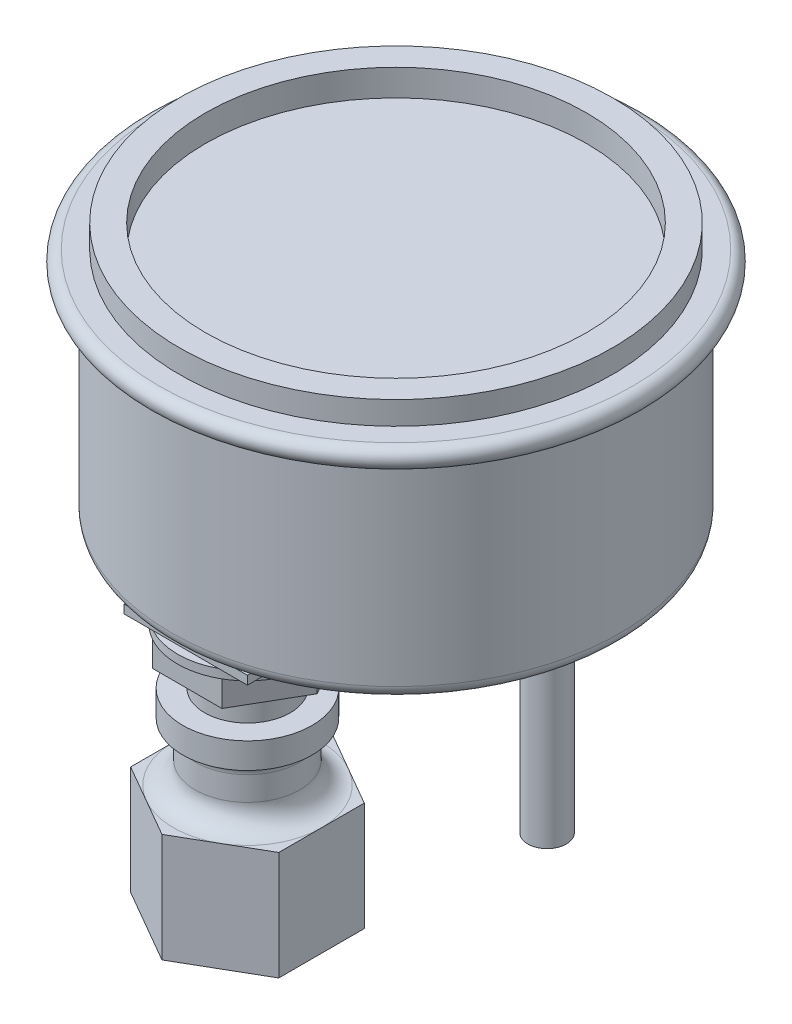
SolidWorks part; units mm, degrees
ref_plane "Front Plane" through (0, 0, 0) normal (0, 0, 1) x (1, 0, 0)
ref_plane "Top Plane" through (0, 0, 0) normal (0, 1, 0) x (1, 0, 0)
ref_plane "Right Plane" through (0, 0, 0) normal (1, 0, 0) x (0, 0, -1)
sketch "Sketch1" plane through (0, 0, 0) normal (0, 0, 1) x (1, 0, 0)
  line L0 (0, 0) -> (0, 26.8)
  line L1 (0, 26.8) -> (22.25, 26.8)
  line L2 (22.25, 26.8) -> (22.25, 29.9)
  line L3 (22.25, 29.9) -> (25.3, 29.9)
  line L4 (25.3, 29.9) -> (25.3, 27.2)
  line L5 (25.3, 27.2) -> (27.65, 27.2)
  line L6 (27.65, 24.8) -> (26.2, 24.8)
  line L7 (26.2, 24.8) -> (26.2, 1.5)
  line L8 (24.7, 0) -> (0, 0)
  line L9 (0, -4.0696) -> (0, 24.0575) construction
  arc A0 (27.65, 27.2) -> (27.65, 24.8) centre (27.65, 26) cw
  arc A1 (26.2, 1.5) -> (24.7, 0) centre (24.7, 1.5) cw
  point P15 (28.85, 26)
  dimension "D4" = 1.2
  dimension "D9" = 1.5
  dimension "D1" = 44.5
  dimension "D2" = 50.6
  dimension "D3" = 57.7
  dimension "D5" = 3.1
  dimension "D6" = 2.7
  dimension "D7" = 29.9
  dimension "D8" = 52.4
revolve "Revolve1" add sketch "Sketch1" angle 360 about L9
sketch "Sketch2" plane through (0, 0, 0) normal (0, -1, 0) x (1, 0, 0)
  line L0 (0, 0) -> (-17.65, 0) construction
  line L1 (0, 0) -> (0, -17.65) construction
  circle A2 centre (-17.65, 0) radius 4.3
  circle A3 centre (0, -17.65) radius 4.3
  circle A4 centre (17.65, 0) radius 4.3
  point P1 (-21.95, 0)
  point P2 (21.95, 0)
  dimension "D1" = 8.6
  dimension "D3" = 43.9
  dimension "D2" = 3
extrude "Boss-Extrude1" add sketch "Sketch2" along normal blind 1.8
sketch "Sketch3" plane through (0, -1.8, 0) normal (0, -1, 0) x (1, 0, 0)
  circle A0 centre (-17.65, 0) radius 2.25
  circle A1 centre (17.65, 0) radius 2.25
  dimension "D1" = 4.5
extrude "Boss-Extrude2" add sketch "Sketch3" along normal blind 21.2
sketch "Sketch4" plane through (0, -1.8, 0) normal (0, -1, 0) x (1, 0, 0)
  circle A0 centre (0, -17.65) radius 2.25
  circle A1 centre (-17.65, 0) radius 2.25 construction
extrude "Boss-Extrude3" add sketch "Sketch4" along normal blind 14.8
sketch "Sketch5" plane through (0, 0, 0) normal (0, -1, 0) x (1, 0, 0)
  line L1 (-7.2, 10.15) -> (7.2, 10.15)
  line L2 (-7.2, 10.15) -> (-7.2, 24.55)
  line L3 (-7.2, 24.55) -> (7.2, 24.55)
  line L4 (7.2, 10.15) -> (7.2, 24.55)
  line L5 (-7.2, 10.15) -> (7.2, 24.55) construction
  line L6 (-7.2, 24.55) -> (7.2, 10.15) construction
  circle A0 centre (0, -17.65) radius 4.3 construction
  circle A1 centre (0, -17.65) radius 4.3 construction
  point P0 (0, 17.35)
  point P7 (0, -21.95)
  dimension "D1" = 14.4
  dimension "D2" = 46.5
extrude "Boss-Extrude4" add sketch "Sketch5" along normal blind 1
sketch "Sketch6" plane through (0, -1, 0) normal (0, -1, 0) x (1, 0, 0)
  line L0 (7.2, 10.15) -> (-7.2, 24.55) construction
  circle A0 centre (0, 17.35) radius 8.15
  dimension "D1" = 16.3
extrude "Boss-Extrude5" add sketch "Sketch6" along normal blind 1
sketch "Sketch7" plane through (0, -2, 0) normal (0, -1, 0) x (1, 0, 0)
  line L1 (8.1406, 17.35) -> (4.0703, 24.4)
  line L2 (4.0703, 24.4) -> (-4.0703, 24.4)
  line L3 (-4.0703, 24.4) -> (-8.1406, 17.35)
  line L4 (-8.1406, 17.35) -> (-4.0703, 10.3)
  line L5 (-4.0703, 10.3) -> (4.0703, 10.3)
  line L6 (4.0703, 10.3) -> (8.1406, 17.35)
  circle A0 centre (0, 17.35) radius 7.05 construction
  dimension "D1" = 14.1
extrude "Boss-Extrude6" add sketch "Sketch7" along normal blind 3
ref_plane "Plane1" through (7.5128, 0, 4.3375) normal (0.866, 0, 0.5) x (0.5, 0, -0.866)
sketch "Sketch8" plane through (7.5128, 0, 4.3375) normal (0.866, 0, 0.5) x (0.5, 0, -0.866)
  line L0 (-15.0255, -16.5842) -> (-15.0255, -6.9426) construction
  line L1 (-10.9552, -5) -> (-19.0959, -5) construction
  line L2 (-20.0255, -5) -> (-20.0255, -8.5)
  line L3 (-20.0255, -8.5) -> (-22.5755, -8.5)
  line L4 (-22.5755, -8.5) -> (-22.5755, -11.5)
  line L5 (-21.1255, -12.95) -> (-21.1255, -15.75)
  line L6 (-23.6755, -18.3) -> (-15.0255, -18.3)
  line L7 (-15.0255, -18.3) -> (-15.0255, -5)
  line L8 (-15.0255, -5) -> (-20.0255, -5)
  line L9 (-23.0036, -11.5) -> (-28.7744, -11.5) construction
  line L10 (-24.7, 0) -> (24.7, 0) construction
  arc A0 (-22.5755, -11.5) -> (-21.1255, -12.95) centre (-22.5755, -12.95) cw
  arc A1 (-21.1255, -15.75) -> (-23.6755, -18.3) centre (-23.6755, -15.75) cw
  point P4 (-15.0255, -5)
  dimension "D1" = 3.5
  dimension "D2" = 10
  dimension "D3" = 15.1
  dimension "D4" = 3
  dimension "D5" = 12.2
  dimension "D6" = 17.3
  dimension "D7" = 18.3
revolve "Revolve2" add sketch "Sketch8" angle 360 about L0
sketch "Sketch9" plane through (0, -18.3, 0) normal (0, -1, 0) x (1, 0, 0)
  line L1 (0, 27.3382) -> (-8.65, 22.3441)
  line L2 (-8.65, 22.3441) -> (-8.65, 12.3559)
  line L3 (-8.65, 12.3559) -> (0, 7.3618)
  line L4 (0, 7.3618) -> (8.65, 12.3559)
  line L5 (8.65, 12.3559) -> (8.65, 22.3441)
  line L6 (8.65, 22.3441) -> (0, 27.3382)
  circle A0 centre (0, 17.35) radius 8.65 construction
  circle A1 centre (0, 17.35) radius 5.6
  dimension "D2" = 11.2
  dimension "D1" = 17.3
extrude "Boss-Extrude7" add sketch "Sketch9" along normal blind 12.7
